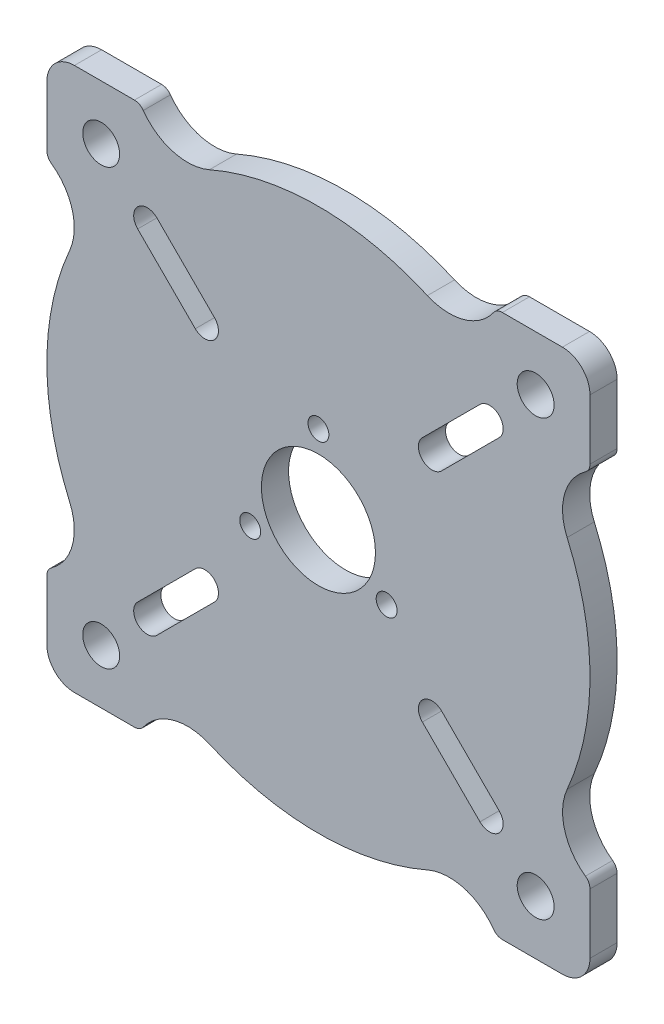
SolidWorks part; units mm, degrees
ref_plane "Plan de face" through (0, 0, 0) normal (0, 0, 1) x (1, 0, 0)
ref_plane "Plan de dessus" through (0, 0, 0) normal (0, 1, 0) x (1, 0, 0)
ref_plane "Plan de droite" through (0, 0, 0) normal (1, 0, 0) x (0, 0, -1)
sketch "Esquisse1" plane through (0, 0, 0) normal (0, 0, 1) x (1, 0, 0)
  line L0 (29.747, -33.2825) -> (19.1403, -22.6759)
  line L1 (22.6759, -19.1403) -> (33.2825, -29.747)
  line L2 (50, -44.9195) -> (50, -33.8621)
  line L3 (33.8724, -50) -> (44.9195, -50)
  line L4 (0, 0) -> (40, -40) construction
  line L5 (-33.2825, -29.747) -> (-22.6759, -19.1403)
  line L6 (33.2825, 29.747) -> (22.6759, 19.1403)
  line L7 (19.1403, 22.6759) -> (29.747, 33.2825)
  line L8 (44.9195, 50) -> (33.8621, 50)
  line L9 (-19.1403, -22.6759) -> (-29.747, -33.2825)
  line L10 (-44.9195, -50) -> (-33.8621, -50)
  line L11 (-50, -33.8724) -> (-50, -44.9195)
  line L12 (0, 0) -> (-40, -40) construction
  line L13 (-29.747, 33.2825) -> (-19.1403, 22.6759)
  line L14 (-22.6759, 19.1403) -> (-33.2825, 29.747)
  line L15 (50, 33.8724) -> (50, 44.9195)
  line L16 (0, 0) -> (40, 40) construction
  line L17 (0, 0) -> (0, 50) construction
  line L18 (0, 0) -> (50, 0) construction
  line L19 (-50, 44.9195) -> (-50, 33.8621)
  line L20 (-33.8724, 50) -> (-44.9195, 50)
  line L21 (0, 0) -> (-40, 40) construction
  circle A0 centre (0, 0) radius 10.5
  arc A1 (45.7956, -20.0691) -> (50, 0) centre (0, 0) ccw
  arc A2 (45.7956, -20.0691) -> (49.1591, -32.2322) centre (54.9547, -24.0829) ccw
  arc A3 (20.0691, 45.7956) -> (0, 50) centre (0, 0) ccw
  arc A4 (20.0691, 45.7956) -> (32.2322, 49.1591) centre (24.0829, 54.9547) ccw
  arc A5 (33.8621, 50) -> (32.2322, 49.1591) centre (33.8621, 48) ccw
  arc A6 (50, 44.9195) -> (44.9195, 50) centre (44.9195, 44.9195) ccw
  arc A7 (49.1585, 32.2421) -> (45.7927, 20.0756) centre (54.9512, 24.0907) ccw
  arc A8 (49.1585, 32.2421) -> (50, 33.8724) centre (48, 33.8724) ccw
  arc A9 (50, 0) -> (45.7927, 20.0756) centre (0, 0) ccw
  arc A10 (50, -33.8621) -> (49.1591, -32.2322) centre (48, -33.8621) ccw
  arc A11 (44.9195, -50) -> (50, -44.9195) centre (44.9195, -44.9195) ccw
  arc A12 (32.2421, -49.1585) -> (20.0756, -45.7927) centre (24.0907, -54.9512) ccw
  arc A13 (32.2421, -49.1585) -> (33.8724, -50) centre (33.8724, -48) ccw
  arc A14 (0, -50) -> (20.0756, -45.7927) centre (0, 0) ccw
  arc A15 (29.747, -33.2825) -> (33.2825, -29.747) centre (31.5147, -31.5147) ccw
  arc A16 (22.6759, -19.1403) -> (19.1403, -22.6759) centre (20.9081, -20.9081) ccw
  circle A17 centre (40, -40) radius 3.4
  arc A18 (-20.0691, -45.7956) -> (0, -50) centre (0, 0) ccw
  arc A19 (-20.0691, -45.7956) -> (-32.2322, -49.1591) centre (-24.0829, -54.9547) ccw
  arc A20 (-33.8621, -50) -> (-32.2322, -49.1591) centre (-33.8621, -48) ccw
  arc A21 (-50, -44.9195) -> (-44.9195, -50) centre (-44.9195, -44.9195) ccw
  arc A22 (-49.1585, -32.2421) -> (-45.7927, -20.0756) centre (-54.9512, -24.0907) ccw
  arc A23 (-49.1585, -32.2421) -> (-50, -33.8724) centre (-48, -33.8724) ccw
  arc A24 (-50, 0) -> (-45.7927, -20.0756) centre (0, 0) ccw
  arc A25 (-33.2825, -29.747) -> (-29.747, -33.2825) centre (-31.5147, -31.5147) ccw
  arc A26 (-19.1403, -22.6759) -> (-22.6759, -19.1403) centre (-20.9081, -20.9081) ccw
  circle A27 centre (-40, -40) radius 3.4
  arc A28 (-45.7956, 20.0691) -> (-50, 0) centre (0, 0) ccw
  arc A29 (-45.7956, 20.0691) -> (-49.1591, 32.2322) centre (-54.9547, 24.0829) ccw
  arc A30 (-50, 33.8621) -> (-49.1591, 32.2322) centre (-48, 33.8621) ccw
  arc A31 (33.2825, 29.747) -> (29.747, 33.2825) centre (31.5147, 31.5147) ccw
  arc A32 (19.1403, 22.6759) -> (22.6759, 19.1403) centre (20.9081, 20.9081) ccw
  circle A33 centre (0, 14.5) radius 1.925
  arc A34 (-44.9195, 50) -> (-50, 44.9195) centre (-44.9195, 44.9195) ccw
  arc A35 (-32.2421, 49.1585) -> (-20.0756, 45.7927) centre (-24.0907, 54.9512) ccw
  arc A36 (-32.2421, 49.1585) -> (-33.8724, 50) centre (-33.8724, 48) ccw
  circle A37 centre (40, 40) radius 3.4
  arc A38 (0, 50) -> (-20.0756, 45.7927) centre (0, 0) ccw
  arc A39 (-29.747, 33.2825) -> (-33.2825, 29.747) centre (-31.5147, 31.5147) ccw
  circle A40 centre (0, 0) radius 14.5 construction
  arc A41 (-22.6759, 19.1403) -> (-19.1403, 22.6759) centre (-20.9081, 20.9081) ccw
  circle A42 centre (-40, 40) radius 3.4
  circle A43 centre (12.5574, -7.25) radius 1.925
  circle A44 centre (-12.5574, -7.25) radius 1.925
  point P97 (0, 0)
  point P102 (0, 0)
  dimension "D1" = 2.5
  dimension "D2" = 29.5685
  dimension "D3" = 40
  dimension "D5" = 50
  dimension "D6" = 50
  dimension "D7" = 4
  dimension "D9" = 29
  dimension "D12" = 50
  dimension "D13" = 10
  dimension "D10" = 21
  dimension "D11" = 50
  dimension "D14" = 10
  dimension "D15" = 3.85
  dimension "D16" = 3
  dimension "D4" = 40
  dimension "D8" = 15
extrude "Boss.-Extru.2" add sketch "Esquisse1" along normal blind 5 contours A3 A38 A35 A36 L20 A34 L19 A30 A29 A28 A24 A22 A23 L11 A21 L10 A20 A19 A18 A14 A12 A13 L3 A11 L2 A10 A2 A1 A9 A7 A8 L15 A6 L8 A5 A4 A44 A43 A42 A41 L14 A39 L13 A0 A16
